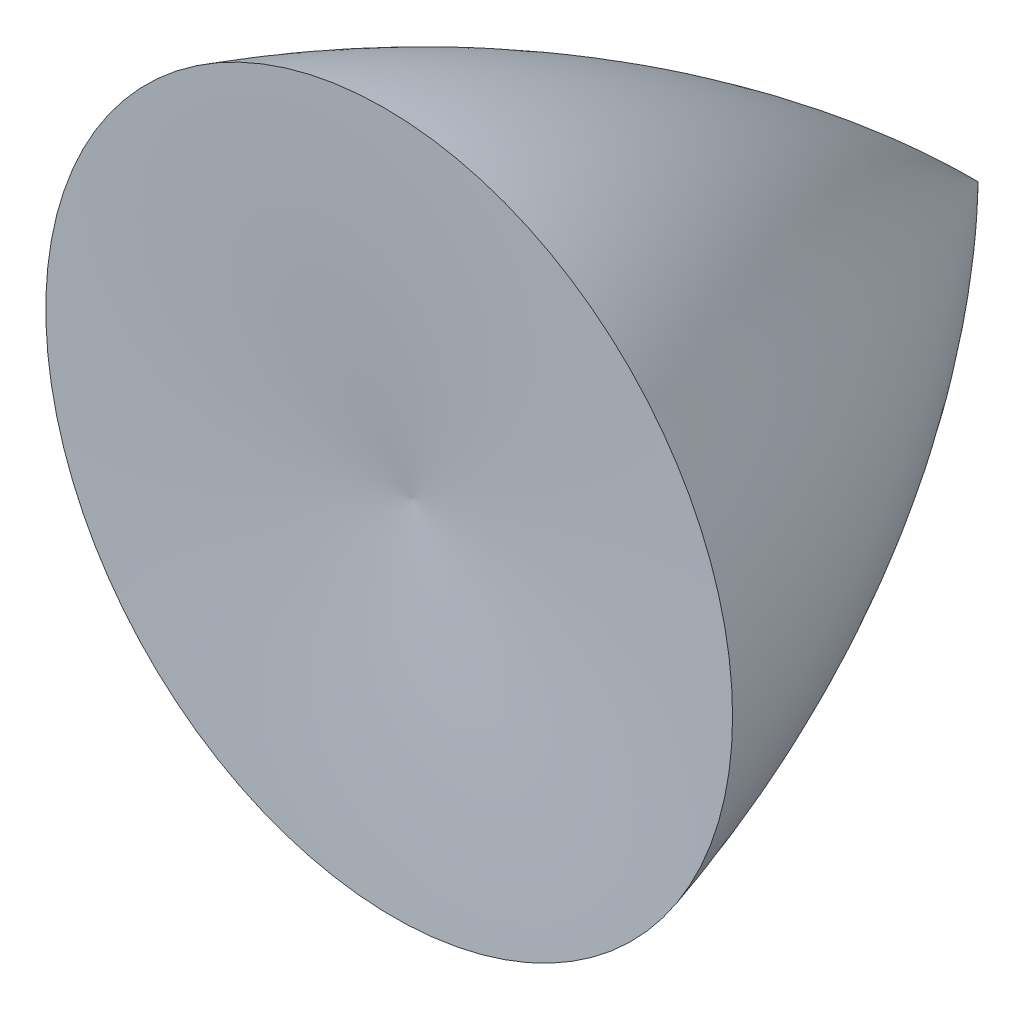
SolidWorks part; units mm, degrees
ref_plane "Front Plane" through (0, 0, 0) normal (0, 0, 1) x (1, 0, 0)
ref_plane "Top Plane" through (0, 0, 0) normal (0, 1, 0) x (1, 0, 0)
ref_plane "Right Plane" through (0, 0, 0) normal (1, 0, 0) x (0, 0, -1)
sketch "Sketch1" plane through (0, 0, 0) normal (0, 1, 0) x (1, 0, 0)
  line L0 (0, 0) -> (1.3513, 100.4887) construction
  line L1 (1.3513, 100.4887) -> (0, 0)
  arc A0 (1.3513, 100.4887) -> (-62.743, -3.3045) centre (171.5094, -76.2735) ccw
  arc A1 (-62.743, -3.3045) -> (0, 0) centre (-76.1397, 848.3673) ccw
  point P6 (1.3513, 100.4887)
revolve "Revolve1" add sketch "Sketch1" angle 360 about L0
